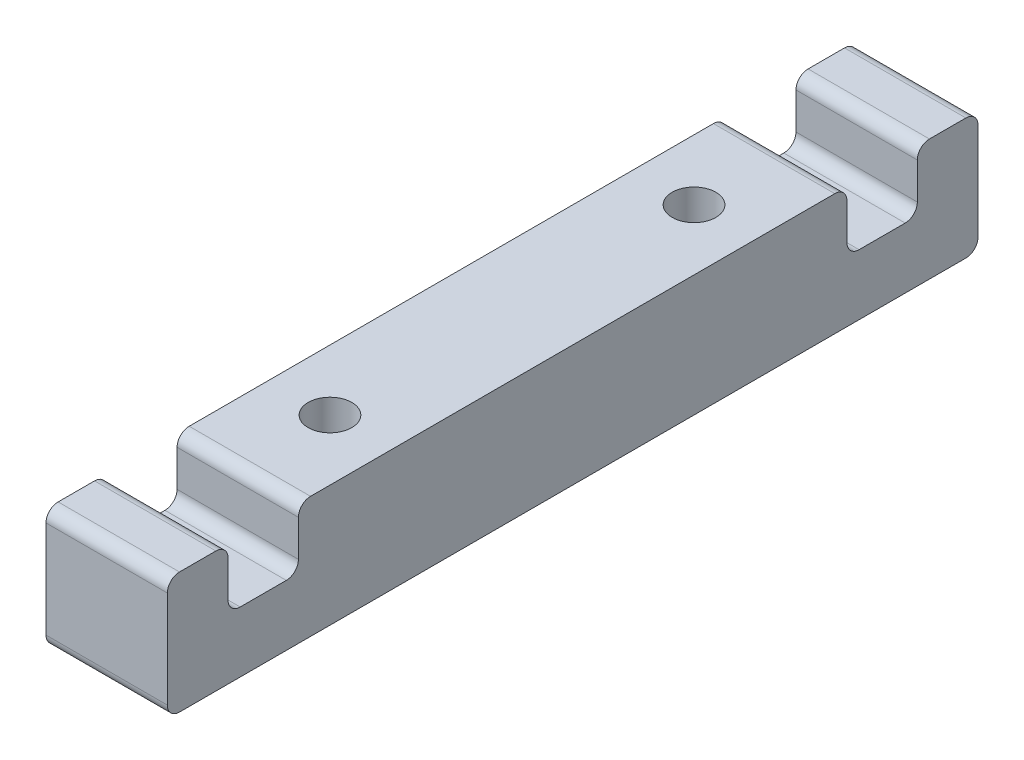
SolidWorks part; units mm, degrees
ref_plane "Front Plane" through (0, 0, 0) normal (0, 0, 1) x (1, 0, 0)
ref_plane "Top Plane" through (0, 0, 0) normal (0, 1, 0) x (1, 0, 0)
ref_plane "Right Plane" through (0, 0, 0) normal (1, 0, 0) x (0, 0, -1)
sketch "Sketch1" plane through (0, 0, 0) normal (1, 0, 0) x (0, 0, -1)
  line L0 (42.418, 0) -> (-42.418, 0)
  line L1 (-42.418, 0) -> (-42.418, 12.7)
  line L2 (-42.418, 12.7) -> (-36.068, 12.7)
  line L3 (-36.068, 12.7) -> (-36.068, 6.35)
  line L4 (-36.068, 6.35) -> (-28.702, 6.35)
  line L5 (-28.702, 6.35) -> (-28.702, 12.7)
  line L6 (-28.702, 12.7) -> (28.702, 12.7)
  line L7 (0, 12.7) -> (0, 0) construction
  line L8 (42.418, 0) -> (42.418, 12.7)
  line L9 (42.418, 12.7) -> (36.068, 12.7)
  line L10 (36.068, 12.7) -> (36.068, 6.35)
  line L11 (36.068, 6.35) -> (28.702, 6.35)
  line L12 (28.702, 6.35) -> (28.702, 12.7)
  point P15 (-32.385, 6.35)
  dimension "D1" = 7.366
  dimension "D2" = 6.35
  dimension "D3" = 6.35
  dimension "D4" = 32.385
  dimension "D5" = 6.35
extrude "Boss-Extrude1" add sketch "Sketch1" along normal blind 12.7
sketch "Sketch2" plane through (0, 12.7, 0) normal (0, 1, 0) x (1, 0, 0)
  line L0 (0, 0) -> (12.7, 0) construction
  line L1 (12.7, 28.702) -> (12.7, -28.702) construction
  circle A0 centre (6.35, -19.05) radius 2.286
  circle A1 centre (6.35, 19.05) radius 2.286
  point P7 (0, 0)
  point P8 (6.35, 0)
  dimension "D1" = 4.572
  dimension "D2" = 19.05
extrude "Cut-Extrude1" cut sketch "Sketch2" against normal blind 12.7
fillet "Fillet1" radius 1.27 12 edges at (6.35, 6.35, 28.702) (6.35, 6.35, 36.068) (6.35, 6.35, -28.702) (6.35, 6.35, -36.068) (6.35, 12.7, -28.702) (6.35, 12.7, 28.702) (6.35, 12.7, 36.068) (6.35, 12.7, 42.418) (6.35, 0, 42.418) (6.35, 0, -42.418) (6.35, 12.7, -42.418) (6.35, 12.7, -36.068)
